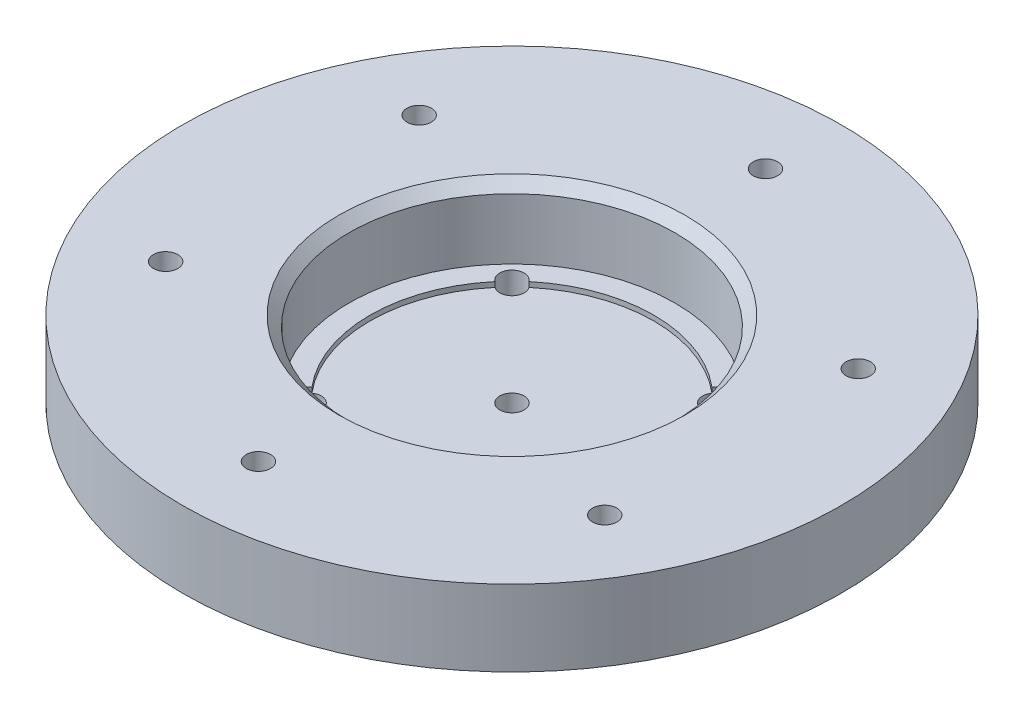
SolidWorks part; units mm, degrees
ref_plane "Ebene vorne" through (0, 0, 0) normal (0, 0, 1) x (1, 0, 0)
ref_plane "Ebene oben" through (0, 0, 0) normal (0, 1, 0) x (1, 0, 0)
ref_plane "Ebene rechts" through (0, 0, 0) normal (1, 0, 0) x (0, 0, -1)
sketch "Skizze1" plane through (0, 0, 0) normal (0, 0, 1) x (1, 0, 0)
  line L0 (0, 0) -> (0, -19560.6512) construction
  line L1 (0, 0) -> (20, 0)
  line L2 (20, 0) -> (20, 7.5)
  line L3 (20, 7.5) -> (32.5, 7.5)
  line L4 (32.5, 7.5) -> (32.5, 15)
  line L5 (32.5, 15) -> (16.075, 15)
  line L6 (16.075, 15) -> (16.075, 8)
  line L7 (14, 7.5) -> (0, 7.5)
  line L8 (0, 7.5) -> (0, 0)
  line L9 (14, 7.5) -> (14, 8)
  line L10 (14, 8) -> (16.075, 8)
  dimension "D1" = 40
  dimension "D2" = 65
  dimension "D3" = 15
  dimension "D4" = 7.5
  dimension "D5" = 32.15
  dimension "D6" = 0.5
  dimension "D7" = 28
revolve "Rotation1" add sketch "Skizze1" angle 360 about L0
hole_wizard "Ø2.4 (2.4) Durchmesser Bohrung1" positions "Skizze2" profile "Skizze3" hole size "Ø2.4" standard "ISO" end condition through all
sketch "Skizze2" plane through (0, 15, 0) normal (0, 1, 0) x (1, 0, 0)
  line L0 (0, 0) -> (0, -50000) construction
  point P5 (0, 25)
  dimension "D1" = 25
sketch "Skizze3" plane through (0, 15, -25) normal (1, 0, 0) x (0, 0, 1)
  line L0 (0, 0) -> (0, 15)
  line L1 (0, 15) -> (1.2, 15)
  line L2 (1.2, 15) -> (1.2, 0)
  line L5 (1.2, 0) -> (0, 0)
  line L11 (0, -6.35) -> (0, 107.95) construction
  dimension "Bohrerdurchmesser" = 2.4
  dimension "Bohrungstiefe" = 15
pattern_circular "Kreismuster1" count 6 over 360 about axis through (0, 0, 0) along (0, 1, 0) of "Ø2.4 (2.4) Durchmesser Bohrung1"
hole_wizard "Ø2.4 (2.4) Durchmesser Bohrung2" positions "Skizze4" profile "Skizze5" hole size "Ø2.4" standard "ISO" end condition through all
sketch "Skizze4" plane through (0, 0, 0) normal (0, -1, 0) x (-1, 0, 0)
  line L1 (-10, -10) -> (10, -10)
  line L2 (-10, -10) -> (-10, 10)
  line L3 (-10, 10) -> (10, 10)
  line L4 (10, -10) -> (10, 10)
  line L5 (-10, -10) -> (10, 10) construction
  line L6 (-10, 10) -> (10, -10) construction
  point P1 (0, 0)
  point P2 (10, 10)
  point P49 (-10, -10)
  point P50 (-10, 10)
  point P51 (10, -10)
  dimension "D1" = 20
  dimension "D2" = 20
sketch "Skizze5" plane through (0, 0, 0) normal (1, 0, 0) x (0, 0, -1)
  line L0 (0, 0) -> (0, 15)
  line L1 (0, 15) -> (1.2, 15)
  line L2 (1.2, 15) -> (1.2, 0)
  line L5 (1.2, 0) -> (0, 0)
  line L11 (0, -6.35) -> (0, 107.95) construction
  dimension "Bohrerdurchmesser" = 2.4
  dimension "Bohrungstiefe" = 15
chamfer "Fase1" distance 1 angle 45 1 edges at (0, 15, 16.075)
chamfer "Fase2" distance 1 angle 45 1 edges at (0, 0, 20)
